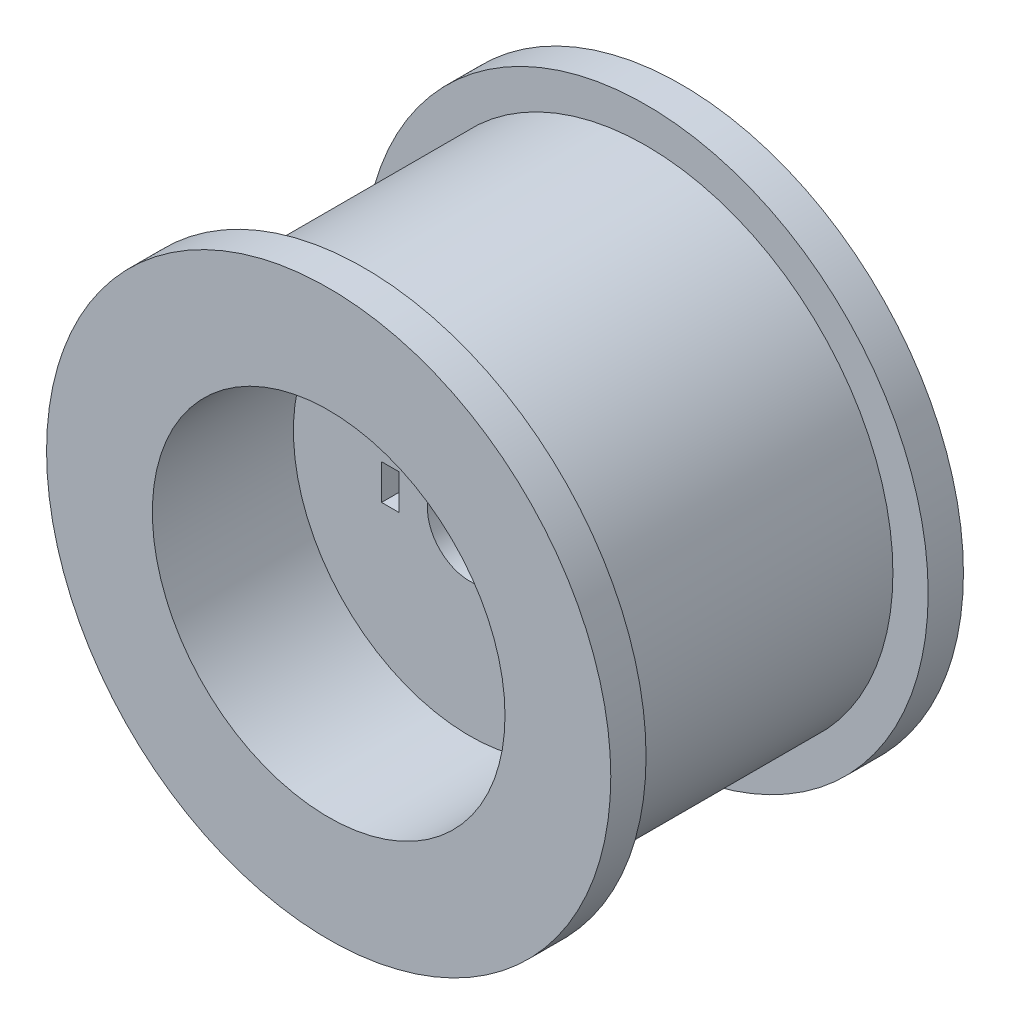
SolidWorks part; units mm, degrees
material "Nylon 6/10"
ref_plane "Front Plane" through (0, 0, 0) normal (0, 0, 1) x (1, 0, 0)
ref_plane "Top Plane" through (0, 0, 0) normal (0, 1, 0) x (1, 0, 0)
ref_plane "Right Plane" through (0, 0, 0) normal (1, 0, 0) x (0, 0, -1)
sketch "Sketch1" plane through (0, 0, 0) normal (0, 0, 1) x (1, 0, 0)
  circle A0 centre (0, 0) radius 35
extrude "Boss-Extrude1" add sketch "Sketch1" along normal blind 40
sketch "Sketch2" plane through (0, 0, 40) normal (0, 0, 1) x (1, 0, 0)
  circle A1 centre (0, 0) radius 40
extrude "Boss-Extrude2" add sketch "Sketch2" along normal blind 5
sketch "Sketch3" plane through (0, 0, 0) normal (0, 0, -1) x (-1, 0, 0)
  circle A0 centre (0, 0) radius 40
extrude "Boss-Extrude3" add sketch "Sketch3" along normal blind 5
sketch "Sketch4" plane through (0, 0, 45) normal (0, 0, 1) x (1, 0, 0)
  circle A0 centre (0, 0) radius 25
extrude "Cut-Extrude1" cut sketch "Sketch4" against normal blind 20
sketch "Sketch5" plane through (0, 0, -5) normal (0, 0, -1) x (-1, 0, 0)
  circle A0 centre (0, 0) radius 25
extrude "Cut-Extrude2" cut sketch "Sketch5" against normal blind 20
sketch "Sketch6" plane through (0, 0, 25) normal (0, 0, 1) x (1, 0, 0)
  circle A0 centre (0, 0) radius 6
extrude "Cut-Extrude3" cut sketch "Sketch6" against normal blind 20
sketch "Sketch7" plane through (0, 0, 25) normal (0, 0, 1) x (1, 0, 0)
  line L10 (-10, -0.0731) -> (-10, -2.5731)
  line L11 (-10, -2.5731) -> (-12.5, -2.5731)
  line L12 (-12.5, -0.0731) -> (-12.5, -2.5731)
  line L14 (-10, -0.0731) -> (-10, 2.4269)
  line L15 (-10, 2.4269) -> (-12.5, 2.4269)
  line L16 (-12.5, -0.0731) -> (-12.5, 2.4269)
  circle A0 centre (0, 0) radius 6 construction
  dimension "D4" = 10
  dimension "D1" = 2.5
  dimension "D2" = 2.5
  dimension "D3" = 2.5
extrude "Cut-Extrude4" cut sketch "Sketch7" against normal blind 10
